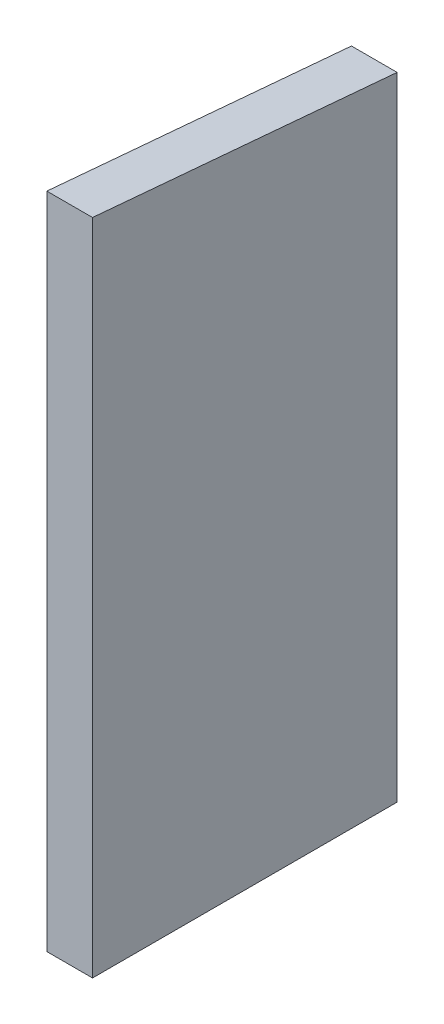
SolidWorks part; units mm, degrees
material "Cedro"
ref_plane "Alzado" through (0, 0, 0) normal (0, 0, 1) x (1, 0, 0)
ref_plane "Planta" through (0, 0, 0) normal (0, 1, 0) x (1, 0, 0)
ref_plane "Vista lateral" through (0, 0, 0) normal (1, 0, 0) x (0, 0, -1)
sketch "Croquis1" plane through (0, 0, 0) normal (0, 1, 0) x (1, 0, 0)
  line L1 (-7.5, -50) -> (7.5, -50)
  line L2 (-7.5, -50) -> (-7.5, 50)
  line L3 (-7.5, 50) -> (7.5, 50)
  line L4 (7.5, -50) -> (7.5, 50)
  line L5 (-7.5, -50) -> (7.5, 50) construction
  line L6 (-7.5, 50) -> (7.5, -50) construction
  point P0 (0, 0)
  dimension "D1" = 15
  dimension "D2" = 100
extrude "Saliente-Extruir1" add sketch "Croquis1" along normal blind 250
sketch "Croquis2" plane through (7.5, 0, 0) normal (1, 0, 0) x (0, 0, -1)
  line L0 (-50, 216.2023) -> (50, 207.4535)
  line L1 (-50, 250) -> (-50, 0) construction
  line L2 (-251.75, 233.8532) -> (-133.1986, 223.4813) construction
  line L3 (50, 250) -> (50, 0) construction
  line L4 (50, 207.4535) -> (50, 250)
  line L5 (50, 250) -> (-50, 250)
  line L6 (-50, 250) -> (-50, 216.2023)
  dimension "D1" = 95
extrude "Cortar-Extruir1" cut sketch "Croquis2" against normal through all
